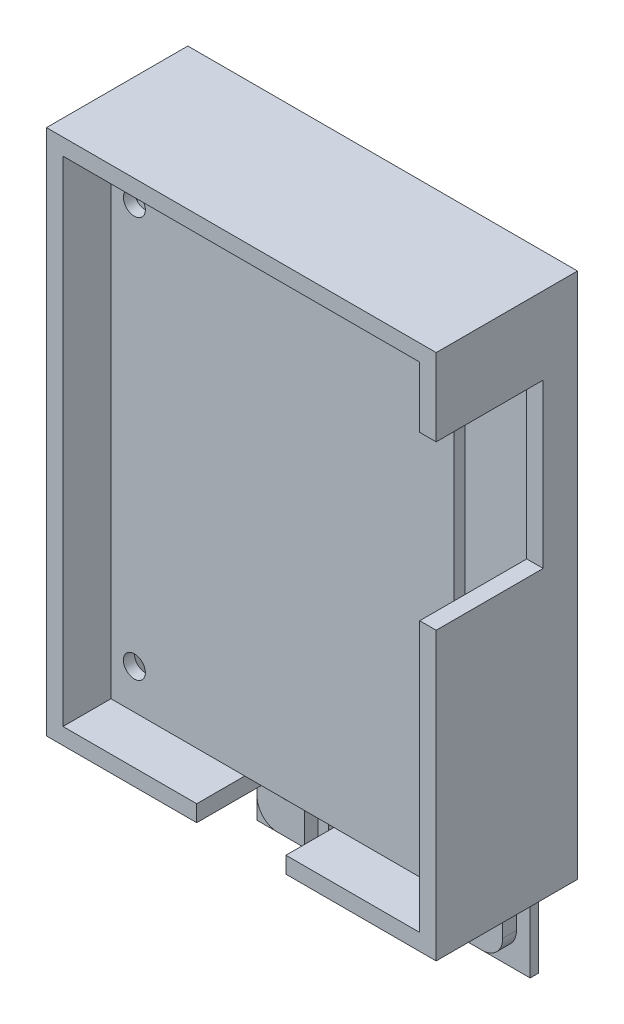
SolidWorks part; units mm, degrees
other "PCB"
other "Box"
other "ESP32"
other "Switch-Cover"
ref_plane "Front Plane" through (0, 0, 0) normal (0, 0, 1) x (1, 0, 0)
ref_plane "Top Plane" through (0, 0, 0) normal (0, 1, 0) x (1, 0, 0)
ref_plane "Right Plane" through (0, 0, 0) normal (1, 0, 0) x (0, 0, -1)
sketch "Sketch1" plane through (0, 0, 0) normal (0, 0, 1) x (1, 0, 0)
  line L1 (-25, -35) -> (25, -35)
  line L2 (-25, -35) -> (-25, 35)
  line L3 (-25, 35) -> (25, 35)
  line L4 (25, -35) -> (25, 35)
  line L5 (0, 35) -> (0, -35) construction
  line L6 (-25, 0) -> (25, 0) construction
  line L7 (-21.59, -29.21) -> (21.59, -29.21) construction
  line L8 (-21.59, -29.21) -> (-21.59, 29.21) construction
  line L9 (-21.59, 29.21) -> (21.59, 29.21) construction
  line L10 (21.59, -29.21) -> (21.59, 29.21) construction
  line L11 (0, 29.21) -> (0, -29.21) construction
  line L12 (-21.59, 0) -> (21.59, 0) construction
  circle A0 centre (-21.59, 29.21) radius 1.6
  circle A1 centre (21.59, 29.21) radius 1.6
  circle A2 centre (21.59, -29.21) radius 1.6
  circle A3 centre (-21.59, -29.21) radius 1.6
  point P0 (0, 0)
  point P4 (0, 0)
  dimension "D1" = 3.2
  dimension "D2" = 50
  dimension "D3" = 70
  dimension "D4" = 43.18
  dimension "D5" = 58.42
extrude "Boss-Extrude1" add sketch "Sketch1" along normal blind 1.6
ref_plane "Plane1" through (0, 0, -12.6) normal (0, 0, -1) x (-1, 0, 0)
ref_plane "Plane2" through (0, 0, 7.6) normal (0, 0, 1) x (1, 0, 0)
sketch "Sketch2" plane through (0, 0, 7.6) normal (0, 0, 1) x (1, 0, 0)
  line L4 (28.4, -38.4) -> (28.4, 38.4)
  line L5 (28.4, 38.4) -> (-28.4, 38.4)
  line L6 (-28.4, 38.4) -> (-28.4, -38.4)
  line L7 (-28.4, -38.4) -> (28.4, -38.4)
  line L8 (26, -36) -> (26, 36)
  line L9 (-26, -36) -> (26, -36)
  line L10 (-26, 36) -> (-26, -36)
  line L11 (26, 36) -> (-26, 36)
  line L12 (26, -36) -> (26, 36)
  line L13 (-26, -36) -> (26, -36)
  line L14 (-26, 36) -> (-26, -36)
  line L15 (26, 36) -> (-26, 36)
  dimension "D1" = 1
  dimension "D2" = 2.4
extrude "Boss-Extrude2" add sketch "Sketch2" against normal up to surface (20.2 mm away) separate body up to plane "Plane1"
sketch "Sketch3" plane through (0, 0, -12.6) normal (0, 0, -1) x (-1, 0, 0)
  line L1 (-28.4, -38.4) -> (28.4, -38.4)
  line L2 (-28.4, -38.4) -> (-28.4, 38.4)
  line L3 (-28.4, 38.4) -> (28.4, 38.4)
  line L4 (28.4, -38.4) -> (28.4, 38.4)
  line L5 (0, 38.4) -> (0, -38.4) construction
  line L6 (-28.4, 0) -> (28.4, 0) construction
  circle A0 centre (-21.59, -29.21) radius 1.6 construction
  circle A1 centre (21.59, -29.21) radius 1.6 construction
  circle A2 centre (21.59, 29.21) radius 1.6 construction
  circle A3 centre (-21.59, 29.21) radius 1.6 construction
  circle A4 centre (-21.59, -29.21) radius 1.6
  circle A5 centre (21.59, -29.21) radius 1.6
  circle A6 centre (21.59, 29.21) radius 1.6
  circle A7 centre (-21.59, 29.21) radius 1.6
  point P0 (0, 0)
extrude "Boss-Extrude3" add sketch "Sketch3" along normal blind 2
ref_plane "Plane3" through (0, 0, -7.7) normal (0, 0, -1) x (-1, 0, 0)
sketch "Sketch4" plane through (0, 0, -7.7) normal (0, 0, -1) x (-1, 0, 0)
  line L0 (21.59, 2.65) -> (21.59, 1.27) construction
  line L1 (-9.41, -15.35) -> (25.59, -15.35)
  line L2 (-9.41, -15.35) -> (-9.41, 2.65)
  line L3 (-9.41, 2.65) -> (25.59, 2.65)
  line L4 (25.59, -15.35) -> (25.59, 2.65)
  line L5 (8.09, 2.65) -> (8.09, -15.35) construction
  line L6 (-9.41, -6.35) -> (25.59, -6.35) construction
  line L7 (21.59, 1.27) -> (21.59, -13.97) construction
  line L8 (21.59, -13.97) -> (21.59, -15.35) construction
  line L9 (21.59, -29.21) -> (21.59, 29.21) construction
  line L10 (21.59, 29.21) -> (-21.59, 29.21) construction
  point P0 (8.09, -6.35)
  dimension "D1" = 18
  dimension "D2" = 15.24
  dimension "D3" = 4
  dimension "D4" = 35
  dimension "D5" = 27.94
extrude "Boss-Extrude4" add sketch "Sketch4" along normal blind 1 separate body
sketch "Sketch5" plane through (-26, 0, 0) normal (1, 0, 0) x (0, 0, -1)
  line L0 (14.9, 1.15) -> (14.9, 4.65)
  line L1 (0.5, 10) -> (5.5, 10)
  line L2 (0.5, 10) -> (0.5, 25)
  line L3 (0.5, 25) -> (5.5, 25)
  line L4 (5.5, 10) -> (5.5, 25)
  line L5 (3, 25) -> (3, 10) construction
  line L6 (0.5, 17.5) -> (5.5, 17.5) construction
  line L7 (11.9, -10.85) -> (8.7, -10.85) construction
  line L8 (11.9, -10.85) -> (11.9, -1.85) construction
  line L9 (11.9, -1.85) -> (8.7, -1.85) construction
  line L10 (8.7, -10.85) -> (8.7, -1.85) construction
  line L11 (10.3, -1.85) -> (10.3, -10.85) construction
  line L12 (11.9, -6.35) -> (8.7, -6.35) construction
  line L13 (5.7, -13.85) -> (14.9, -13.85)
  line L14 (5.7, -13.85) -> (5.7, 1.15)
  line L15 (5.7, 1.15) -> (14.9, 1.15) construction
  line L16 (14.9, -13.85) -> (14.9, 1.15)
  line L17 (10.3, 1.15) -> (10.3, -13.85) construction
  line L18 (5.7, -6.35) -> (14.9, -6.35) construction
  line L19 (14.9, 4.65) -> (5.7, 4.65)
  line L20 (5.7, 4.65) -> (5.7, 1.15)
  line L21 (8.7, -15.35) -> (8.7, 2.65) construction
  line L22 (8.7, 2.65) -> (7.7, 2.65) construction
  line L23 (11.9, -10.85) -> (14.9, -10.85) construction
  line L24 (11.9, -10.85) -> (11.9, -13.85) construction
  line L26 (0, -35) -> (0, 35) construction
  point P0 (3, 17.5)
  point P4 (10.3, -6.35)
  point P8 (10.3, -6.35)
  dimension "D1" = 3.2
  dimension "D2" = 3
  dimension "D3" = 9
  dimension "D4" = 2
  dimension "D5" = 3
  dimension "D6" = 15
  dimension "D7" = 17.5
  dimension "D8" = 5
extrude "Cut-Extrude1" cut sketch "Sketch5" against normal through all and the other way blind 2
sketch "Sketch6" plane through (0, -36, 0) normal (0, 1, 0) x (1, 0, 0)
  line L0 (-26, -7.6) -> (26, -7.6) construction
  line L1 (-6.5, 8) -> (6.5, 8)
  line L2 (-6.5, 8) -> (-6.5, -7.6)
  line L3 (-6.5, -7.6) -> (6.5, -7.6)
  line L4 (6.5, 8) -> (6.5, -7.6)
  line L5 (0, -7.6) -> (0, 8) construction
  line L6 (-6.5, 0.2) -> (6.5, 0.2) construction
  line L8 (-25, 0) -> (25, 0) construction
  point P0 (0, 0.2)
  dimension "D1" = 8
  dimension "D2" = 13
extrude "Cut-Extrude2" cut sketch "Sketch6" against normal through all
sketch "Sketch7" plane through (26, 0, 0) normal (-1, 0, 0) x (0, 0, 1)
  line L0 (7.6, -36) -> (7.6, 36) construction
  line L1 (-8, 27.13) -> (7.6, 27.13)
  line L2 (-8, 27.13) -> (-8, 3.35)
  line L3 (-8, 3.35) -> (7.6, 3.35)
  line L4 (7.6, 27.13) -> (7.6, 3.35)
  line L5 (-0.2, 3.35) -> (-0.2, 27.13) construction
  line L6 (-8, 15.24) -> (7.6, 15.24) construction
  line L8 (4.5593, 27.13) -> (4.5593, 24.13) construction
  line L9 (4.5593, 24.13) -> (4.5593, 21.59) construction
  line L10 (4.5593, 21.59) -> (4.5593, 19.05) construction
  line L11 (4.5593, 19.05) -> (4.5593, 16.51) construction
  line L12 (4.5593, 16.51) -> (4.5593, 13.97) construction
  line L13 (4.5593, 13.97) -> (4.5593, 11.43) construction
  line L14 (4.5593, 11.43) -> (4.5593, 8.89) construction
  line L15 (4.5593, 8.89) -> (4.5593, 6.35) construction
  line L16 (4.5593, 6.35) -> (4.5593, 3.35) construction
  line L17 (0, -35) -> (0, 35) construction
  point P216 (-0.2, 15.24)
  dimension "D1" = 3
  dimension "D2" = 2.54
  dimension "D3" = 5.08
  dimension "D4" = 8
  dimension "D5" = 7
extrude "Cut-Extrude3" cut sketch "Sketch7" against normal through all
sketch "Sketch11" plane through (0, 0, -12.6) normal (0, 0, 1) x (1, 0, 0)
  line L0 (9.41, -15.35) -> (9.41, 2.65) construction
  line L2 (9.41, 2.65) -> (-25.59, 2.65) construction
  line L3 (-24, 4.65) -> (-22.59, 4.65)
  line L4 (-22.59, 4.65) -> (-22.59, -0.95)
  line L5 (-22.59, -0.95) -> (-24, -2.36)
  line L6 (-24, -13.85) -> (-24, 4.65) construction
  line L7 (-24, -2.36) -> (-24, 4.65)
  line L10 (-25.59, -15.35) -> (-25.59, 2.65) construction
  circle A0 centre (7.41, -4.35) radius 4
  point P9 (-22.59, 1.85)
  dimension "D1" = 8
  dimension "D2" = 2
  dimension "D3" = 7
  dimension "D4" = 45
  dimension "D5" = 0.8
  dimension "D6" = 3
extrude "Cut-Extrude5" cut sketch "Sketch11" against normal through all
sketch "Sketch8" plane through (0, 0, -14.6) normal (0, 0, -1) x (-1, 0, 0)
  line L0 (0, 35) -> (0, -35) construction
  line L1 (-19.9, -39.4) -> (19.9, -39.4)
  line L2 (-19.9, -39.4) -> (-19.9, -55.9)
  line L3 (-19.9, -55.9) -> (19.9, -55.9)
  line L4 (19.9, -39.4) -> (19.9, -55.9)
  line L5 (0, -55.9) -> (0, -39.4) construction
  line L6 (-19.9, -47.65) -> (19.9, -47.65) construction
  line L7 (28.4, -38.4) -> (-28.4, -38.4) construction
  line L9 (-9.5, -54.15) -> (9.5, -54.15)
  line L10 (-9.5, -54.15) -> (-9.5, -41.15)
  line L11 (-9.5, -41.15) -> (9.5, -41.15)
  line L12 (9.5, -54.15) -> (9.5, -41.15)
  line L13 (0, -41.15) -> (0, -54.15) construction
  line L14 (-9.5, -47.65) -> (9.5, -47.65) construction
  point P0 (0, -47.65)
  point P11 (0, -47.65)
  dimension "D1" = 16.5
  dimension "D2" = 39.8
  dimension "D3" = 1
  dimension "D4" = 13
  dimension "D5" = 19
extrude "Boss-Extrude5" add sketch "Sketch8" along normal blind 1.2 separate body
sketch "Sketch9" plane through (0, 0, -14.6) normal (0, 0, -1) x (-1, 0, 0)
  line L0 (-19.9, -47.65) -> (19.9, -47.65) construction
  line L1 (-17.9, -53.9) -> (-11, -53.9)
  line L2 (-17.9, -53.9) -> (-17.9, -41.4)
  line L3 (-17.9, -41.4) -> (-11, -41.4)
  line L4 (-11, -53.9) -> (-11, -41.4)
  line L5 (-14.45, -41.4) -> (-14.45, -53.9) construction
  line L6 (-17.9, -47.65) -> (-11, -47.65) construction
  line L7 (11, -53.9) -> (17.9, -53.9)
  line L8 (11, -53.9) -> (11, -41.4)
  line L9 (11, -41.4) -> (17.9, -41.4)
  line L10 (17.9, -53.9) -> (17.9, -41.4)
  line L11 (14.45, -41.4) -> (14.45, -53.9) construction
  line L12 (11, -47.65) -> (17.9, -47.65) construction
  line L13 (-11, -41.4) -> (11, -41.4) construction
  line L14 (0, -55.9) -> (0, -39.4) construction
  line L15 (-19.9, -39.4) -> (19.9, -39.4) construction
  line L16 (-19.9, -39.4) -> (-19.9, -55.9) construction
  point P0 (-14.45, -47.65)
  point P4 (14.45, -47.65)
  point P10 (0, -41.4)
  dimension "D1" = 22
  dimension "D2" = 2
  dimension "D3" = 2
extrude "Boss-Extrude6" add sketch "Sketch9" against normal blind 2
sketch "Sketch10" plane through (0, 0, -12.6) normal (0, 0, 1) x (1, 0, 0)
  line L0 (-16.95, -49.15) -> (-12.7572, -49.15) construction
  line L1 (19.9, -47.65) -> (-19.9, -47.65) construction
  line L2 (-14.45, -41.4) -> (-14.45, -53.9) construction
  line L3 (12.75, -49.15) -> (16.8724, -49.15) construction
  line L4 (14.45, -41.4) -> (14.45, -53.9) construction
  text T0 "<b>IG</b>"
  text T1 "<b>A</b>"
  dimension "D1" = 1.5
  dimension "D2" = 2.5
  dimension "D3" = 1.7
extrude "Cut-Extrude4" cut sketch "Sketch10" against normal blind 2
fillet "Fillet1" radius 3 4 edges at (17.9, -41.4, -13.6) (17.9, -53.9, -13.6) (-17.9, -53.9, -13.6) (-17.9, -41.4, -13.6)
chamfer "Chamfer1" distance 1.6 angle 45 5 edges at (-28.4, -26.125, -14.6) (0, -38.4, -14.6) (28.4, 0, -14.6) (0, 38.4, -14.6) (-28.4, 21.525, -14.6)
